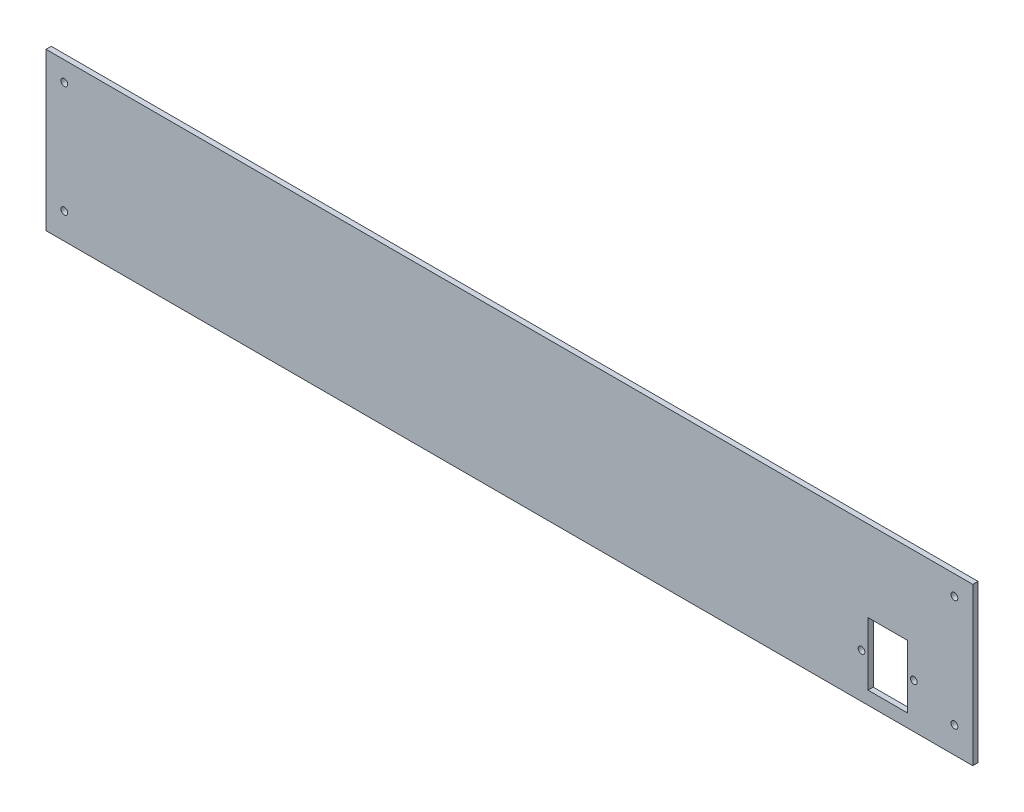
SolidWorks part; units mm, degrees
ref_plane "Front Plane" through (0, 0, 0) normal (0, 0, 1) x (1, 0, 0)
ref_plane "Top Plane" through (0, 0, 0) normal (0, 1, 0) x (1, 0, 0)
ref_plane "Right Plane" through (0, 0, 0) normal (1, 0, 0) x (0, 0, -1)
sketch "Sketch1" plane through (0, 0, 0) normal (0, 0, 1) x (1, 0, 0)
  line L1 (0, 0) -> (708, 0)
  line L2 (0, 0) -> (0, 120)
  line L3 (0, 120) -> (708, 120)
  line L4 (708, 0) -> (708, 120)
  dimension "D1" = 708
  dimension "D2" = 120
extrude "Boss-Extrude1" add sketch "Sketch1" along normal blind 4
sketch "Sketch2" plane through (0, 0, 4) normal (0, 0, 1) x (1, 0, 0)
  line L0 (708, 0) -> (708, 120) construction
  line L1 (628, 58) -> (658, 58)
  line L2 (628, 58) -> (628, 10)
  line L3 (628, 10) -> (658, 10)
  line L4 (658, 58) -> (658, 10)
  line L5 (0, 0) -> (708, 0) construction
  line L6 (623, 34) -> (663, 34)
  circle A0 centre (623, 34) radius 2.55
  circle A1 centre (663, 34) radius 2.55
  point P12 (643, 58)
  dimension "D7" = 5.1
  dimension "D8" = 5.1
  dimension "D1" = 30
  dimension "D2" = 48
  dimension "D3" = 50
  dimension "D4" = 10
  dimension "D5" = 40
  dimension "D6" = 20
  dimension "D9" = 24
extrude "Cut-Extrude1" cut sketch "Sketch2" against normal up to next
ref_plane "Plane1" through (354, 0, 0) normal (1, 0, 0) x (0, 0, -1)
ref_plane "Plane2" through (0, 60, 0) normal (0, 1, 0) x (1, 0, 0)
sketch "Sketch5" plane through (0, 0, 0) normal (0, 0, -1) x (-1, 0, 0)
  line L0 (-708, 120) -> (0, 120) construction
  line L3 (-708, 0) -> (-708, 120) construction
  line L4 (0, 120) -> (0, 0) construction
  circle A0 centre (-694, 105) radius 2.6
  circle A1 centre (-14, 105) radius 2.6
  dimension "D3" = 5.2
  dimension "D6" = 5.2
  dimension "D1" = 15
  dimension "D2" = 14
  dimension "D4" = 15
  dimension "D5" = 14
extrude "Cut-Extrude3" cut sketch "Sketch5" against normal blind 10
sketch "Sketch6" plane through (0, 0, 0) normal (0, 0, -1) x (-1, 0, 0)
  line L2 (0, 0) -> (-708, 0) construction
  line L3 (-708, 0) -> (-708, 120) construction
  circle A0 centre (-694, 20) radius 2.6
  dimension "D3" = 5.2
  dimension "D1" = 20
  dimension "D2" = 14
extrude "Cut-Extrude4" cut sketch "Sketch6" against normal blind 10
mirror "Mirror7" about plane through (354, 0, 0) normal (1, 0, 0) of "Cut-Extrude4"
